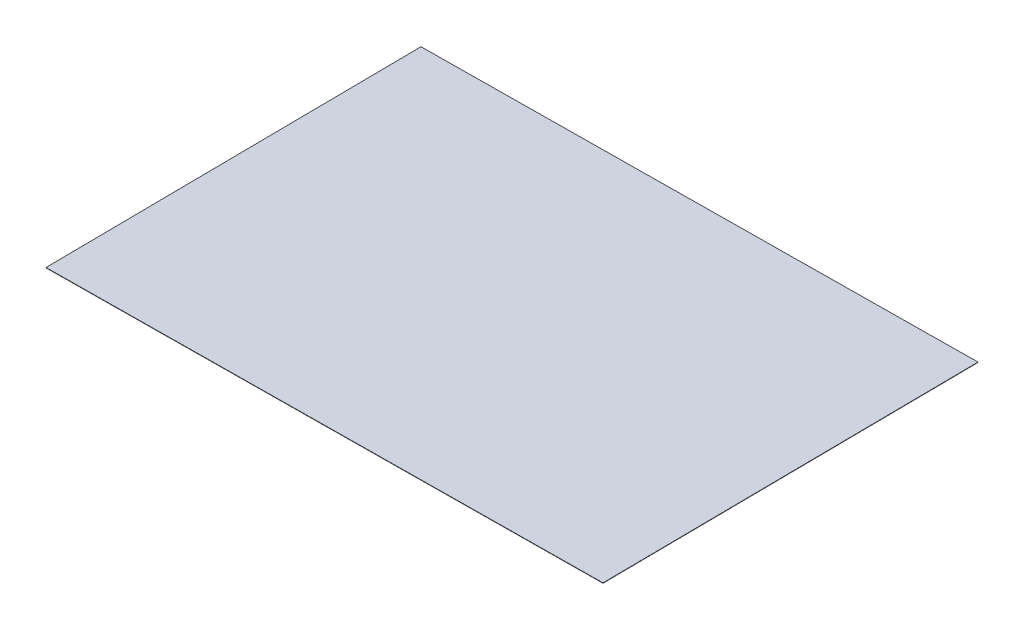
SolidWorks part; units mm, degrees
ref_plane "Спереди" through (0, 0, 0) normal (0, 0, 1) x (1, 0, 0)
ref_plane "Сверху" through (0, 0, 0) normal (0, 1, 0) x (1, 0, 0)
ref_plane "Справа" through (0, 0, 0) normal (1, 0, 0) x (0, 0, -1)
sketch "Эскиз1" plane through (0, 0, 0) normal (0, 1, 0) x (1, 0, 0)
  line L1 (-8.5, 6) -> (8.5, 6)
  line L2 (-8.5, 6) -> (-8.5, -6)
  line L3 (-8.5, -6) -> (8.5, -6)
  line L4 (8.5, 6) -> (8.5, -6)
  line L5 (-8.5, 6) -> (8.5, -6) construction
  line L6 (-8.5, -6) -> (8.5, 6) construction
  point P0 (0, 0)
  dimension "D1" = 12
  dimension "D2" = 17
extrude "Бобышка-Вытянуть1" add sketch "Эскиз1" along normal blind 0.01
sketch "Эскиз2" plane through (0, 0.01, 0) normal (0, 1, 0) x (1, 0, 0)
  line L0 (-7.7385, 5.1279) -> (7.6396, 5.2784)
  line L1 (7.6396, 5.2784) -> (7.7422, -5.21)
  line L2 (7.7422, -5.21) -> (-7.6358, -5.3605)
  line L3 (-7.6358, -5.3605) -> (-7.7385, 5.1279)
  line L5 (-11.7135, 8.0588) -> (11.7135, 8.0588)
  line L6 (-11.7135, 8.0588) -> (-11.7135, -8.0588)
  line L7 (-11.7135, -8.0588) -> (11.7135, -8.0588)
  line L8 (11.7135, 8.0588) -> (11.7135, -8.0588)
  line L9 (-11.7135, 8.0588) -> (11.7135, -8.0588) construction
  line L10 (-11.7135, -8.0588) -> (11.7135, 8.0588) construction
  point P2 (0, 0)
extrude "Вырез-Вытянуть1" cut sketch "Эскиз2" against normal blind 0.01
sketch "Эскиз3" plane through (0, 0.01, 0) normal (0, 1, 0) x (1, 0, 0)
  line L0 (7.6396, 5.2784) -> (7.7422, -5.21)
  line L1 (7.6396, 5.2784) -> (7.5396, 5.2774)
  line L2 (7.7422, -5.21) -> (7.6422, -5.211)
  line L3 (7.5396, 5.2774) -> (7.6422, -5.211)
  dimension "D1" = 0.1
extrude "Вырез-Вытянуть2" cut sketch "Эскиз3" against normal blind 0.01
